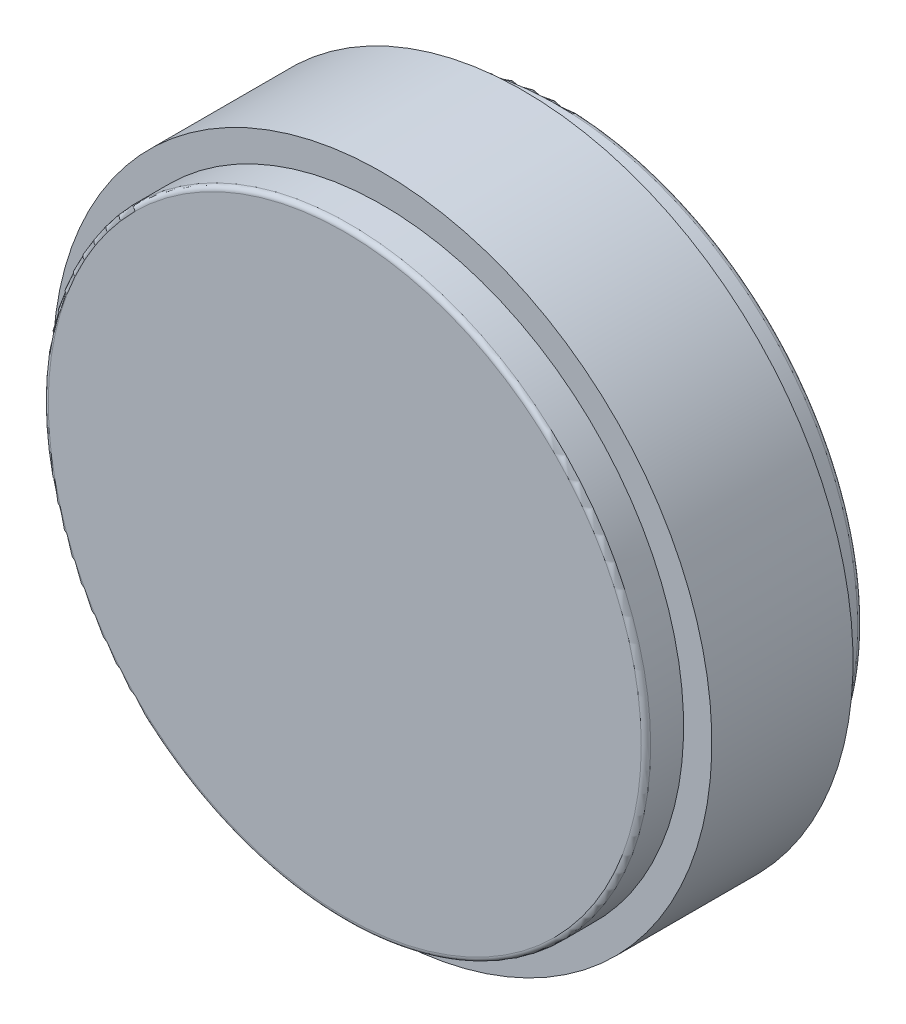
SolidWorks part; units mm, degrees
ref_plane "Спереди" through (0, 0, 0) normal (0, 0, 1) x (1, 0, 0)
ref_plane "Сверху" through (0, 0, 0) normal (0, 1, 0) x (1, 0, 0)
ref_plane "Справа" through (0, 0, 0) normal (1, 0, 0) x (0, 0, -1)
sketch "Эскиз1" plane through (0, 0, 0) normal (0, 1, 0) x (1, 0, 0)
  line L0 (0, 0) -> (-32, 0)
  line L1 (-32, 0) -> (-32, 4)
  line L2 (-32, 4) -> (-35, 4)
  line L3 (-35, 4) -> (-35, 19)
  line L4 (-35, 19) -> (-32, 19)
  line L5 (-32, 19) -> (-32, 23)
  line L6 (-32, 23) -> (0, 23)
  line L7 (0, 23) -> (0, 0)
  dimension "D1" = 32
  dimension "D2" = 4
  dimension "D3" = 15
  dimension "D4" = 35
revolve "Повернуть1" add sketch "Эскиз1" angle 360 about L7
fillet "Скругление1" radius 0.5 2 edges at (-32, 0, 0) (-32, 0, -23)
sketch "Эскиз2" plane through (0, 0, -23) normal (0, 0, -1) x (-1, 0, 0)
  circle A0 centre (0, 0) radius 12.5
  dimension "D1" = 25
extrude "Вырез-Вытянуть1" cut sketch "Эскиз2" against normal blind 0.5
sketch "Эскиз3" plane through (0, 0, 0) normal (1, 0, 0) x (0, 0, -1)
  line L0 (22.5, 0) -> (19.5, 0)
  line L1 (22.5, -12.5) -> (22.5, 12.5) construction
  line L2 (19.5, 0) -> (22.5, 3)
  line L3 (22.5, 3) -> (22.5, 0)
  dimension "D1" = 3
  dimension "D2" = 45
revolve "Вырез-Повернуть1" cut sketch "Эскиз3" angle 360 about L0
